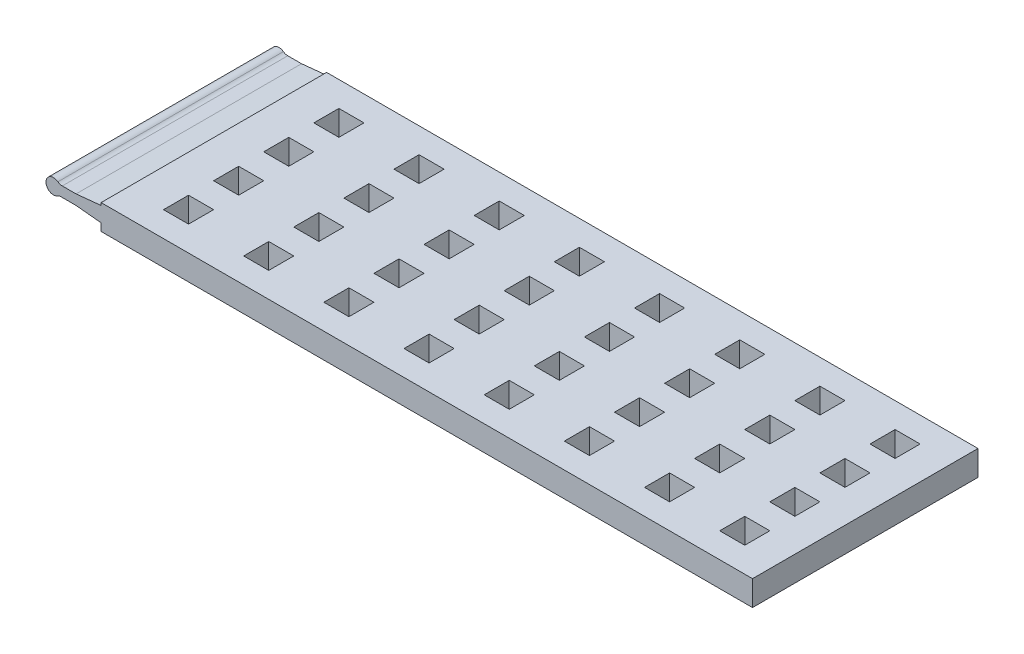
SolidWorks part; units mm, degrees
ref_plane "Front Plane" through (0, 0, 0) normal (0, 0, 1) x (1, 0, 0)
ref_plane "Top Plane" through (0, 0, 0) normal (0, 1, 0) x (1, 0, 0)
ref_plane "Right Plane" through (0, 0, 0) normal (1, 0, 0) x (0, 0, -1)
sketch "Sketch1" plane through (0, 0, 0) normal (0, 1, 0) x (1, 0, 0)
  line L1 (-101.1824, -44.1801) -> (113.8176, -44.1801)
  line L2 (-101.1824, -44.1801) -> (-101.1824, 45.8199)
  line L3 (-101.1824, 45.8199) -> (113.8176, 45.8199)
  line L4 (113.8176, -44.1801) -> (113.8176, 45.8199)
  dimension "D1" = 215
  dimension "D2" = 90
extrude "Boss-Extrude1" add sketch "Sketch1" along normal mid plane 10
sketch "Sketch3" plane through (0, 0, 44.1801) normal (0, 0, 1) x (1, 0, 0)
  line L0 (-101.1824, 5) -> (113.8176, 5) construction
  line L1 (-101.1824, -5) -> (-76.1824, -5)
  line L2 (-101.1824, -5) -> (-101.1824, 5)
  line L3 (-101.1824, 5) -> (-76.1824, 5)
  line L4 (-76.1824, 4) -> (-76.1824, 5)
  line L5 (-91.6805, 3) -> (-86.1824, 3)
  line L6 (-92.0673, -1) -> (-86.1824, -1)
  line L7 (-81.7869, 7.3907) -> (-81.7869, -7.7686) construction
  line L8 (-86.1824, 3) -> (-76.1824, 4)
  line L9 (-76.1824, -2) -> (-76.1824, -5)
  line L10 (-86.1824, -1) -> (-76.1824, -2)
  arc A0 (-93.4314, 3.564) -> (-93.6249, -1.436) centre (-95.1824, 1.128) ccw
  arc A1 (-93.6249, -1.436) -> (-92.0673, -1) centre (-92.0673, -4) cw
  arc A2 (-91.6805, 3) -> (-93.4314, 3.564) centre (-91.6805, 6) cw
  point P11 (-76.1824, 3)
  point P12 (-76.1824, -1)
  dimension "D3" = 6
  dimension "D6" = 3
  dimension "D1" = 25
  dimension "D2" = 6
  dimension "D4" = 4
  dimension "D5" = 2
  dimension "D7" = 10
  dimension "D8" = 1
  dimension "D9" = 10
  dimension "D10" = 1
extrude "Cut-Extrude2" cut sketch "Sketch3" against normal through all
sketch "Sketch6" plane through (0, 5, 0) normal (0, 1, 0) x (1, 0, 0)
  line L5 (-61.28, -34.1801) -> (-51.28, -24.1801) construction
  line L6 (-61.28, -24.1801) -> (-51.28, -34.1801) construction
  point P0 (-56.28, -29.1801)
  dimension "D3" = 10
sketch "Sketch7" plane through (113.8176, 0, 0) normal (1, 0, 0) x (0, 0, -1)
  line L1 (-44.1801, -5) -> (45.8199, -5)
  line L2 (-44.1801, -5) -> (-44.1801, 5)
  line L3 (-44.1801, 5) -> (45.8199, 5)
  line L4 (45.8199, -5) -> (45.8199, 5)
extrude "Boss-Extrude3" add sketch "Sketch7" along normal blind 70
sketch "Sketch8" plane through (0, 5, 0) normal (0, 1, 0) x (1, 0, 0)
  line L0 (-29.28, -34.1801) -> (-29.28, -24.1801)
  line L1 (-61.28, -34.1801) -> (-51.28, -34.1801)
  line L2 (-61.28, -34.1801) -> (-61.28, -24.1801)
  line L3 (-61.28, -24.1801) -> (-51.28, -24.1801)
  line L4 (-51.28, -34.1801) -> (-51.28, -24.1801)
  line L5 (-29.28, -34.1801) -> (-19.28, -34.1801)
  line L6 (-19.28, -34.1801) -> (-19.28, -24.1801)
  line L7 (-29.28, -24.1801) -> (-19.28, -24.1801)
  line L8 (2.72, -34.1801) -> (2.72, -24.1801)
  line L9 (2.72, -34.1801) -> (12.72, -34.1801)
  line L10 (12.72, -34.1801) -> (12.72, -24.1801)
  line L11 (2.72, -24.1801) -> (12.72, -24.1801)
  line L12 (34.72, -34.1801) -> (34.72, -24.1801)
  line L13 (34.72, -34.1801) -> (44.72, -34.1801)
  line L14 (44.72, -34.1801) -> (44.72, -24.1801)
  line L15 (34.72, -24.1801) -> (44.72, -24.1801)
  line L16 (66.72, -34.1801) -> (66.72, -24.1801)
  line L17 (66.72, -34.1801) -> (76.72, -34.1801)
  line L18 (76.72, -34.1801) -> (76.72, -24.1801)
  line L19 (66.72, -24.1801) -> (76.72, -24.1801)
  line L20 (98.72, -34.1801) -> (98.72, -24.1801)
  line L21 (98.72, -34.1801) -> (108.72, -34.1801)
  line L22 (108.72, -34.1801) -> (108.72, -24.1801)
  line L23 (98.72, -24.1801) -> (108.72, -24.1801)
  line L24 (130.72, -34.1801) -> (130.72, -24.1801)
  line L25 (130.72, -34.1801) -> (140.72, -34.1801)
  line L26 (140.72, -34.1801) -> (140.72, -24.1801)
  line L27 (130.72, -24.1801) -> (140.72, -24.1801)
  line L28 (-29.28, -14.1801) -> (-29.28, -4.1801)
  line L29 (-29.28, -14.1801) -> (-19.28, -14.1801)
  line L30 (-19.28, -14.1801) -> (-19.28, -4.1801)
  line L31 (-29.28, -4.1801) -> (-19.28, -4.1801)
  line L32 (2.72, -14.1801) -> (2.72, -4.1801)
  line L33 (2.72, -14.1801) -> (12.72, -14.1801)
  line L34 (12.72, -14.1801) -> (12.72, -4.1801)
  line L35 (2.72, -4.1801) -> (12.72, -4.1801)
  line L36 (34.72, -14.1801) -> (34.72, -4.1801)
  line L37 (34.72, -14.1801) -> (44.72, -14.1801)
  line L38 (44.72, -14.1801) -> (44.72, -4.1801)
  line L39 (34.72, -4.1801) -> (44.72, -4.1801)
  line L40 (66.72, -14.1801) -> (66.72, -4.1801)
  line L41 (66.72, -14.1801) -> (76.72, -14.1801)
  line L42 (76.72, -14.1801) -> (76.72, -4.1801)
  line L43 (66.72, -4.1801) -> (76.72, -4.1801)
  line L44 (98.72, -14.1801) -> (98.72, -4.1801)
  line L45 (98.72, -14.1801) -> (108.72, -14.1801)
  line L46 (108.72, -14.1801) -> (108.72, -4.1801)
  line L47 (98.72, -4.1801) -> (108.72, -4.1801)
  line L48 (130.72, -14.1801) -> (130.72, -4.1801)
  line L49 (130.72, -14.1801) -> (140.72, -14.1801)
  line L50 (140.72, -14.1801) -> (140.72, -4.1801)
  line L51 (130.72, -4.1801) -> (140.72, -4.1801)
  line L52 (-29.28, 5.8199) -> (-29.28, 15.8199)
  line L53 (-29.28, 5.8199) -> (-19.28, 5.8199)
  line L54 (-19.28, 5.8199) -> (-19.28, 15.8199)
  line L55 (-29.28, 15.8199) -> (-19.28, 15.8199)
  line L56 (2.72, 5.8199) -> (2.72, 15.8199)
  line L57 (2.72, 5.8199) -> (12.72, 5.8199)
  line L58 (12.72, 5.8199) -> (12.72, 15.8199)
  line L59 (2.72, 15.8199) -> (12.72, 15.8199)
  line L60 (34.72, 5.8199) -> (34.72, 15.8199)
  line L61 (34.72, 5.8199) -> (44.72, 5.8199)
  line L62 (44.72, 5.8199) -> (44.72, 15.8199)
  line L63 (34.72, 15.8199) -> (44.72, 15.8199)
  line L64 (66.72, 5.8199) -> (66.72, 15.8199)
  line L65 (66.72, 5.8199) -> (76.72, 5.8199)
  line L66 (76.72, 5.8199) -> (76.72, 15.8199)
  line L67 (66.72, 15.8199) -> (76.72, 15.8199)
  line L68 (98.72, 5.8199) -> (98.72, 15.8199)
  line L69 (98.72, 5.8199) -> (108.72, 5.8199)
  line L70 (108.72, 5.8199) -> (108.72, 15.8199)
  line L71 (98.72, 15.8199) -> (108.72, 15.8199)
  line L72 (130.72, 5.8199) -> (130.72, 15.8199)
  line L73 (130.72, 5.8199) -> (140.72, 5.8199)
  line L74 (140.72, 5.8199) -> (140.72, 15.8199)
  line L75 (130.72, 15.8199) -> (140.72, 15.8199)
  line L76 (-29.28, 25.8199) -> (-29.28, 35.8199)
  line L77 (-29.28, 25.8199) -> (-19.28, 25.8199)
  line L78 (-19.28, 25.8199) -> (-19.28, 35.8199)
  line L79 (-29.28, 35.8199) -> (-19.28, 35.8199)
  line L80 (2.72, 25.8199) -> (2.72, 35.8199)
  line L81 (2.72, 25.8199) -> (12.72, 25.8199)
  line L82 (12.72, 25.8199) -> (12.72, 35.8199)
  line L83 (2.72, 35.8199) -> (12.72, 35.8199)
  line L84 (34.72, 25.8199) -> (34.72, 35.8199)
  line L85 (34.72, 25.8199) -> (44.72, 25.8199)
  line L86 (44.72, 25.8199) -> (44.72, 35.8199)
  line L87 (34.72, 35.8199) -> (44.72, 35.8199)
  line L88 (66.72, 25.8199) -> (66.72, 35.8199)
  line L89 (66.72, 25.8199) -> (76.72, 25.8199)
  line L90 (76.72, 25.8199) -> (76.72, 35.8199)
  line L91 (66.72, 35.8199) -> (76.72, 35.8199)
  line L92 (98.72, 25.8199) -> (98.72, 35.8199)
  line L93 (98.72, 25.8199) -> (108.72, 25.8199)
  line L94 (108.72, 25.8199) -> (108.72, 35.8199)
  line L95 (98.72, 35.8199) -> (108.72, 35.8199)
  line L96 (130.72, 25.8199) -> (130.72, 35.8199)
  line L97 (130.72, 25.8199) -> (140.72, 25.8199)
  line L98 (140.72, 25.8199) -> (140.72, 35.8199)
  line L99 (130.72, 35.8199) -> (140.72, 35.8199)
  line L100 (-61.28, -14.1801) -> (-61.28, -4.1801)
  line L101 (-61.28, -14.1801) -> (-51.28, -14.1801)
  line L102 (-51.28, -14.1801) -> (-51.28, -4.1801)
  line L103 (-61.28, -4.1801) -> (-51.28, -4.1801)
  line L104 (-61.28, 5.8199) -> (-61.28, 15.8199)
  line L105 (-61.28, 5.8199) -> (-51.28, 5.8199)
  line L106 (-51.28, 5.8199) -> (-51.28, 15.8199)
  line L107 (-61.28, 15.8199) -> (-51.28, 15.8199)
  line L108 (-61.28, 25.8199) -> (-61.28, 35.8199)
  line L109 (-61.28, 25.8199) -> (-51.28, 25.8199)
  line L110 (-51.28, 25.8199) -> (-51.28, 35.8199)
  line L111 (-61.28, 35.8199) -> (-51.28, 35.8199)
  dimension "D1" = 7
  dimension "D2" = 4
extrude "Cut-Extrude4" cut sketch "Sketch8" against normal blind 38
ref_plane "Plane1" through (150.72, 0, 0) normal (-1, 0, 0) x (0, 0, 1)
mirror "Mirror2" about plane through (150.72, 0, 0) normal (-1, 0, 0) of "Cut-Extrude4"
